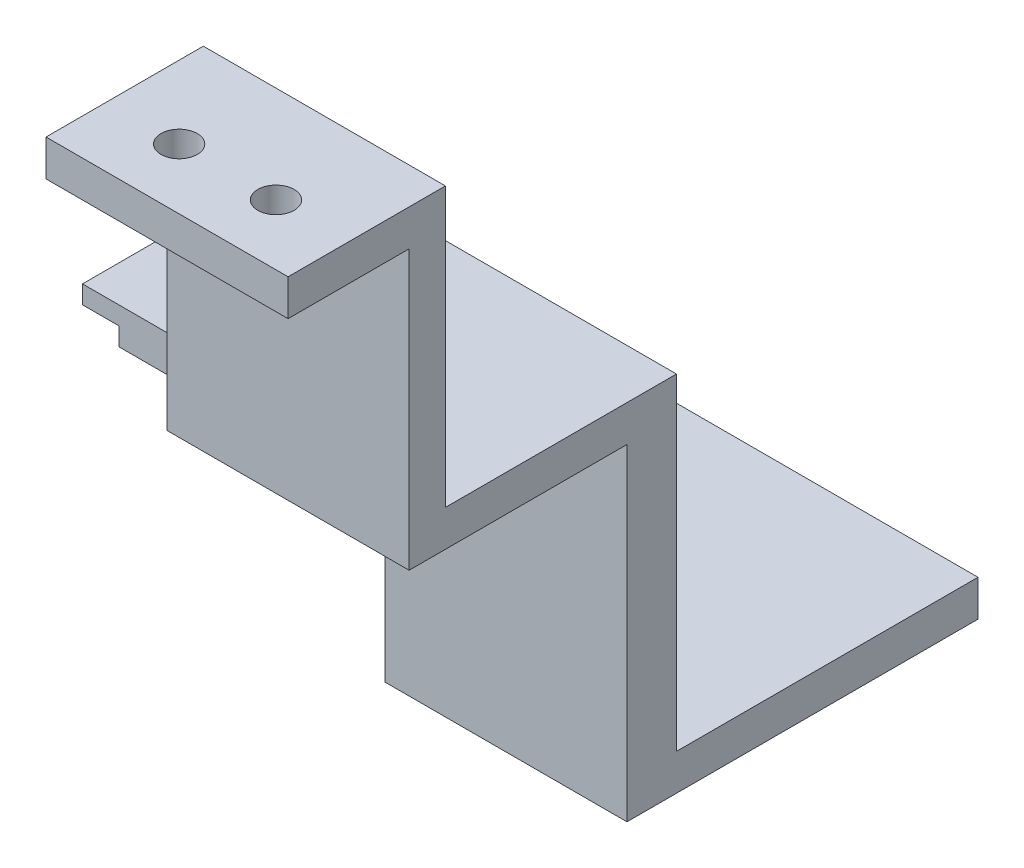
SolidWorks part; units mm, degrees
ref_plane "前视基准面" through (0, 0, 0) normal (0, 0, 1) x (1, 0, 0)
ref_plane "上视基准面" through (0, 0, 0) normal (0, 1, 0) x (1, 0, 0)
ref_plane "右视基准面" through (0, 0, 0) normal (1, 0, 0) x (0, 0, -1)
other "Configuration Table"
sketch "草图1" plane through (0, 0, 0) normal (0, 1, 0) x (1, 0, 0)
  line L1 (-10, 5) -> (10, 5)
  line L2 (-10, 5) -> (-10, -5)
  line L3 (-10, -5) -> (10, -5)
  line L4 (10, 5) -> (10, -5)
  line L5 (-10, 5) -> (10, -5) construction
  line L6 (-10, -5) -> (10, 5) construction
  point P0 (0, 0)
  dimension "D1" = 10
  dimension "D2" = 20
extrude "凸台-拉伸1" add sketch "草图1" along normal blind 3
sketch "草图2" plane through (-10, 0, 0) normal (-1, 0, 0) x (0, 0, 1)
  line L1 (-5, 0) -> (5, 0) construction
  line L3 (-8, -20) -> (-8, 3)
  line L4 (-104, 3) -> (16, 3) construction
  line L5 (-8, 3) -> (-5, 3)
  line L6 (-5, 3) -> (-5, 0)
  line L8 (-8, -23) -> (-5, -23)
  line L10 (-23, -50) -> (-44, -50)
  line L12 (-5, -23) -> (-5, 0)
  line L15 (-27.0878, -20) -> (-8, -20)
  line L16 (-27.0878, -20) -> (-27.0878, -47)
  line L17 (-8, -23) -> (-23, -23)
  line L18 (-23, 0) -> (-23, -50) construction
  line L19 (-23, -23) -> (-23, -50)
  line L20 (-23, -50) -> (-65, -50) construction
  line L21 (-44, -50) -> (-44, -47)
  line L22 (-44, -47) -> (-27.0878, -47)
  dimension "D3" = 3
extrude "凸台-拉伸4" add sketch "草图2" against normal blind 20
sketch "草图4" plane through (0, 3, 0) normal (0, 1, 0) x (1, 0, 0)
  line L0 (0, 8) -> (0, 0) construction
  line L1 (10, 8) -> (-10, 8) construction
  line L2 (0, 0) -> (4, 0) construction
  line L3 (0, 0) -> (-4, 0) construction
  circle A0 centre (4, 0) radius 1.5
  circle A1 centre (-4, 0) radius 1.5
  dimension "D4" = 3
  dimension "D5" = 3
  dimension "D1" = 8
  dimension "D2" = 4
  dimension "D3" = 4
extrude "切除-拉伸1" cut sketch "草图4" against normal up to next
sketch "草图5" plane through (0, -50, 0) normal (0, -1, 0) x (1, 0, 0)
  line L0 (-45.984, -44) -> (10, -44) construction
  line L1 (-45.984, -23) -> (-45.984, -65) construction
  line L2 (-45.984, -52) -> (-45.984, -36)
  line L4 (-45.984, -36) -> (10, -36)
  line L5 (10, -44) -> (10, -23) construction
  line L6 (10, -36) -> (10, -52)
  line L7 (-45.984, -52) -> (10, -52)
  dimension "D1" = 8
extrude "凸台-拉伸5" add sketch "草图5" against normal blind 3
sketch "草图6" plane through (-45.984, 0, 0) normal (-1, 0, 0) x (0, 0, 1)
  line L1 (-52, -47) -> (-36, -47)
  line L2 (-52, -47) -> (-52, -50)
  line L3 (-52, -50) -> (-36, -50)
  line L4 (-36, -47) -> (-36, -50)
extrude "切除-拉伸2" cut sketch "草图6" against normal blind 1
sketch "草图7" plane through (-44.984, 0, 0) normal (-1, 0, 0) x (0, 0, 1)
  line L0 (-36, -50) -> (-36, -47) construction
  line L1 (-52, -47) -> (-36, -47)
  line L2 (-52, -47) -> (-52, -48.5)
  line L3 (-52, -48.5) -> (-36, -48.5)
  line L4 (-36, -47) -> (-36, -48.5)
extrude "凸台-拉伸6" add sketch "草图7" along normal blind 3
